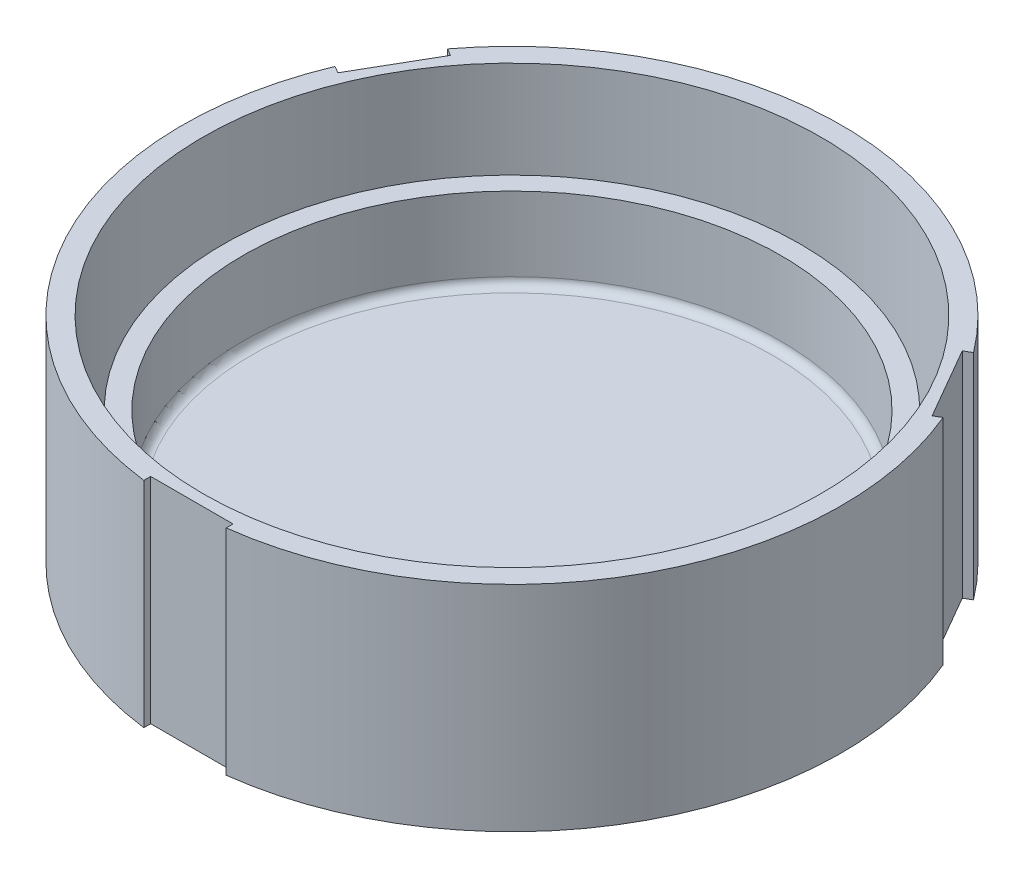
SolidWorks part; units mm, degrees
material "1060-H12"
ref_plane "Front Plane" through (0, 0, 0) normal (0, 0, 1) x (1, 0, 0)
ref_plane "Top Plane" through (0, 0, 0) normal (0, 1, 0) x (1, 0, 0)
ref_plane "Right Plane" through (0, 0, 0) normal (1, 0, 0) x (0, 0, -1)
sketch "Szkic2" plane through (0, 0, 0) normal (0, 1, 0) x (1, 0, 0)
  circle A0 centre (0, 0) radius 80
  dimension "D1" = 160
extrude "Dodanie-wyciągnięcie1" add sketch "Szkic2" along normal blind 52
sketch "Szkic3" plane through (0, 52, 0) normal (0, 1, 0) x (1, 0, 0)
  circle A0 centre (0, 0) radius 75
  dimension "D1" = 150
extrude "Wytnij-wyciągnięcie1" cut sketch "Szkic3" against normal blind 40 contours A0
sketch "Szkic4" plane through (0, 12, 0) normal (0, 1, 0) x (1, 0, 0)
  circle A0 centre (0, 0) radius 70
  circle A1 centre (0, 0) radius 65.25
  dimension "D1" = 140
  dimension "D2" = 130.5
extrude "Dodanie-wyciągnięcie3" add sketch "Szkic4" along normal blind 20 contours A1
fillet "Zaokrąglenie4" radius 2 1 edges at (0, 12, 65.25)
fillet "Zaokrąglenie5" radius 2 2 edges at (0, 12, 75) (0, 12, 70)
sketch "Szkic5" plane through (0, 0, 0) normal (0, -1, 0) x (1, 0, 0)
  line L0 (0, 0) -> (0, 50000) construction
  line L1 (72.117, -29.8797) -> (89.4375, -39.8797)
  line L2 (-10, 77.71) -> (10, 77.71)
  line L3 (-10, 77.71) -> (-10, 97.71)
  line L4 (-10, 97.71) -> (10, 97.71)
  line L5 (10, 77.71) -> (10, 97.71)
  line L6 (-10, 77.71) -> (10, 97.71) construction
  line L7 (-10, 97.71) -> (10, 77.71) construction
  line L8 (72.117, -29.8797) -> (62.117, -47.2003)
  line L9 (62.117, -47.2003) -> (79.4375, -57.2003)
  line L10 (89.4375, -39.8797) -> (79.4375, -57.2003)
  line L11 (-62.117, -47.2003) -> (-79.4375, -57.2003)
  line L12 (-62.117, -47.2003) -> (-72.117, -29.8797)
  line L13 (-72.117, -29.8797) -> (-89.4375, -39.8797)
  line L14 (-79.4375, -57.2003) -> (-89.4375, -39.8797)
  circle A0 centre (0, 0) radius 80 construction
  circle A1 centre (0, 0) radius 80 construction
  point P3 (0, 87.71)
  point P20 (0, 0.21)
  circle M5 centre (0, 0) radius 80
  dimension "D1" = 20
  dimension "D2" = 20
  dimension "D3" = 77.71
  dimension "D5" = 20
  dimension "D6" = 20
  dimension "D7" = 77.395
  dimension "D4" = 3
extrude "Wytnij-wyciągnięcie3" cut sketch "Szkic5" against normal through all contours L14 L11 L13 M5 | L10 L1 L9 M5 | L5 L4 L3 L2
